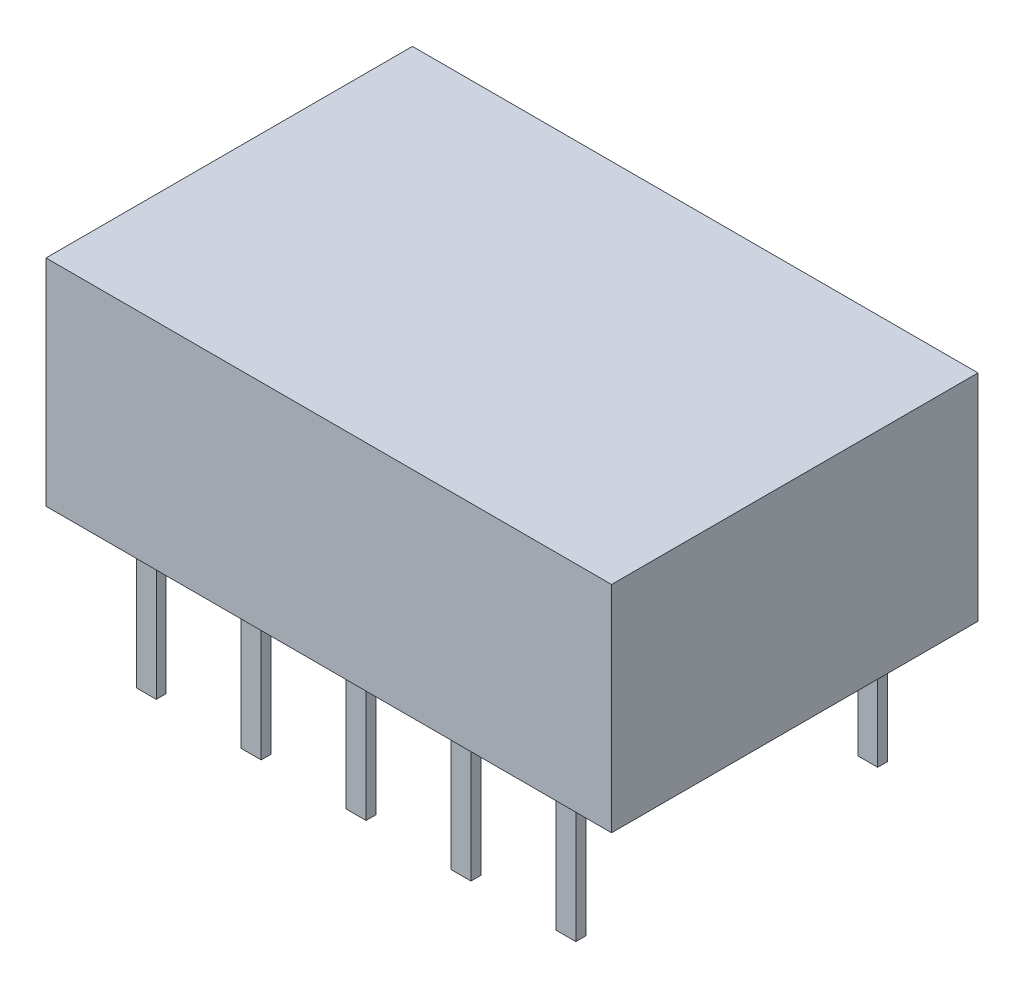
SolidWorks part; units mm, degrees
ref_plane "Front Plane" through (0, 0, 0) normal (0, 0, 1) x (1, 0, 0)
ref_plane "Top Plane" through (0, 0, 0) normal (0, 1, 0) x (1, 0, 0)
ref_plane "Right Plane" through (0, 0, 0) normal (1, 0, 0) x (0, 0, -1)
sketch "Sketch1" plane through (0, 0, 0) normal (0, 0, 1) x (1, 0, 0)
  line L1 (0, 0) -> (14.2, 0)
  line L2 (0, 0) -> (0, 5.4)
  line L3 (0, 5.4) -> (14.2, 5.4)
  line L4 (14.2, 0) -> (14.2, 5.4)
  dimension "D1" = 5.4
  dimension "D2" = 14.2
extrude "Boss-Extrude1" add sketch "Sketch1" along normal blind 9.2
sketch "Sketch2" plane through (0, 0, 0) normal (0, -1, 0) x (1, 0, 0)
  line L0 (1.5826, 8.5144) -> (2.0826, 8.2644) construction
  line L3 (1.5826, 8.5144) -> (2.0826, 8.5144)
  line L4 (1.5826, 8.5144) -> (1.5826, 8.2644)
  line L5 (1.5826, 8.2644) -> (2.0826, 8.2644)
  line L6 (2.0826, 8.5144) -> (2.0826, 8.2644)
  line L7 (2.0826, 8.5144) -> (1.5826, 8.2644) construction
  line L8 (4.2163, 8.5144) -> (4.7163, 8.5144)
  line L9 (4.2163, 8.5144) -> (4.2163, 8.2644)
  line L10 (4.2163, 8.2644) -> (4.7163, 8.2644)
  line L11 (4.7163, 8.5144) -> (4.7163, 8.2644)
  line L12 (4.2163, 8.5144) -> (4.7163, 8.2644) construction
  line L13 (4.7163, 8.5144) -> (4.2163, 8.2644) construction
  line L14 (6.85, 8.5144) -> (7.35, 8.5144)
  line L15 (6.85, 8.5144) -> (6.85, 8.2644)
  line L16 (6.85, 8.2644) -> (7.35, 8.2644)
  line L17 (7.35, 8.5144) -> (7.35, 8.2644)
  line L18 (6.85, 8.5144) -> (7.35, 8.2644) construction
  line L19 (7.35, 8.5144) -> (6.85, 8.2644) construction
  line L20 (9.4837, 8.5144) -> (9.9837, 8.5144)
  line L21 (9.4837, 8.5144) -> (9.4837, 8.2644)
  line L22 (9.4837, 8.2644) -> (9.9837, 8.2644)
  line L23 (9.9837, 8.5144) -> (9.9837, 8.2644)
  line L24 (9.4837, 8.5144) -> (9.9837, 8.2644) construction
  line L25 (9.9837, 8.5144) -> (9.4837, 8.2644) construction
  line L26 (12.1174, 8.5144) -> (12.6174, 8.5144)
  line L27 (12.1174, 8.5144) -> (12.1174, 8.2644)
  line L28 (12.1174, 8.2644) -> (12.6174, 8.2644)
  line L29 (12.6174, 8.5144) -> (12.6174, 8.2644)
  line L30 (12.1174, 8.5144) -> (12.6174, 8.2644) construction
  line L31 (12.6174, 8.5144) -> (12.1174, 8.2644) construction
  line L32 (4.2163, 0.9356) -> (4.7163, 0.9356)
  line L33 (4.2163, 0.9356) -> (4.2163, 0.6856)
  line L34 (4.2163, 0.6856) -> (4.7163, 0.6856)
  line L35 (4.7163, 0.9356) -> (4.7163, 0.6856)
  line L36 (4.2163, 0.9356) -> (4.7163, 0.6856) construction
  line L37 (4.7163, 0.9356) -> (4.2163, 0.6856) construction
  line L38 (6.85, 0.9356) -> (7.35, 0.9356)
  line L39 (6.85, 0.9356) -> (6.85, 0.6856)
  line L40 (6.85, 0.6856) -> (7.35, 0.6856)
  line L41 (7.35, 0.9356) -> (7.35, 0.6856)
  line L42 (6.85, 0.9356) -> (7.35, 0.6856) construction
  line L43 (7.35, 0.9356) -> (6.85, 0.6856) construction
  line L44 (9.4837, 0.9356) -> (9.9837, 0.9356)
  line L45 (9.4837, 0.9356) -> (9.4837, 0.6856)
  line L46 (9.4837, 0.6856) -> (9.9837, 0.6856)
  line L47 (9.9837, 0.9356) -> (9.9837, 0.6856)
  line L48 (9.4837, 0.9356) -> (9.9837, 0.6856) construction
  line L49 (9.9837, 0.9356) -> (9.4837, 0.6856) construction
  line L50 (12.1174, 0.9356) -> (12.6174, 0.9356)
  line L51 (12.1174, 0.9356) -> (12.1174, 0.6856)
  line L52 (12.1174, 0.6856) -> (12.6174, 0.6856)
  line L53 (12.6174, 0.9356) -> (12.6174, 0.6856)
  line L54 (12.1174, 0.9356) -> (12.6174, 0.6856) construction
  line L55 (12.6174, 0.9356) -> (12.1174, 0.6856) construction
  line L56 (1.5826, 0.9356) -> (2.0826, 0.9356)
  line L57 (1.5826, 0.9356) -> (1.5826, 0.6856)
  line L58 (1.5826, 0.6856) -> (2.0826, 0.6856)
  line L59 (2.0826, 0.9356) -> (2.0826, 0.6856)
  line L60 (1.5826, 0.9356) -> (2.0826, 0.6856) construction
  line L61 (2.0826, 0.9356) -> (1.5826, 0.6856) construction
  line L62 (12.3674, 0.8106) -> (1.8326, 8.3894) construction
  line L63 (12.3674, 8.3894) -> (1.8326, 0.8106) construction
  line L64 (7.1, 9.2) -> (7.1, 0) construction
  line L65 (0, 9.2) -> (14.2, 9.2) construction
  line L66 (0, 0) -> (14.2, 0) construction
  line L67 (14.2, 4.6) -> (0, 4.6) construction
  line L68 (14.2, 9.2) -> (14.2, 0) construction
  line L69 (0, 9.2) -> (0, 0) construction
  point P56 (7.1, 4.6)
  point P59 (7.1, 4.5502)
  dimension "D1" = 0.5
  dimension "D2" = 0.25
  dimension "D5" = 0
  dimension "D6" = 0
  dimension "D3" = 5
  dimension "D4" = 2
extrude "Boss-Extrude2" add sketch "Sketch2" along normal blind 3.5
